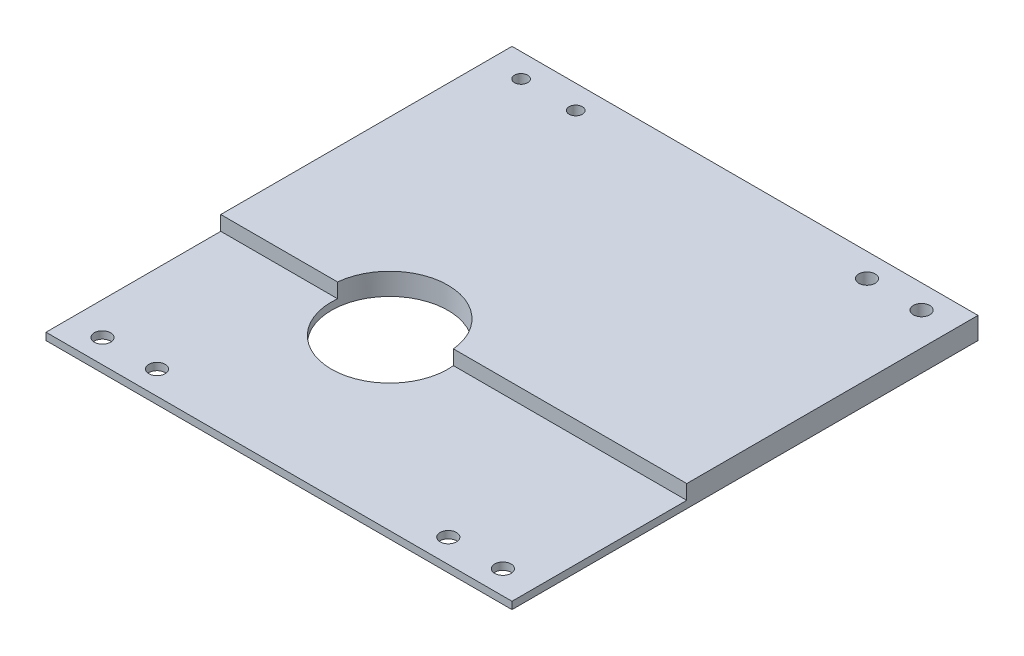
SolidWorks part; units mm, degrees
material "AISI 1020 Steel, Cold Rolled"
ref_plane "Front Plane" through (0, 0, 0) normal (0, 0, 1) x (1, 0, 0)
ref_plane "Top Plane" through (0, 0, 0) normal (0, 1, 0) x (1, 0, 0)
ref_plane "Right Plane" through (0, 0, 0) normal (1, 0, 0) x (0, 0, -1)
sketch "Sketch1" plane through (0, 0, 0) normal (0, 1, 0) x (1, 0, 0)
  line L1 (-203.2, 203.2) -> (203.2, 203.2)
  line L2 (-203.2, 203.2) -> (-203.2, -203.2)
  line L3 (-203.2, -203.2) -> (203.2, -203.2)
  line L4 (203.2, 203.2) -> (203.2, -203.2)
  dimension "D1" = 203.2
  dimension "D2" = 406.4
  dimension "D3" = 203.2
  dimension "D4" = 406.4
extrude "Boss-Extrude1" add sketch "Sketch1" along normal blind 6.35
sketch "Sketch2" plane through (0, 6.35, 0) normal (0, 1, 0) x (1, 0, 0)
  line L0 (-203.2, 203.2) -> (-203.2, -55.88)
  line L1 (-203.2, 203.2) -> (-203.2, -203.2) construction
  line L2 (-203.2, -55.88) -> (-50.8, -55.88)
  circle A0 centre (-50.8, -55.88) radius 50.8
  dimension "D3" = 101.6
  dimension "D1" = 259.08
  dimension "D2" = 152.4
extrude "Cut-Extrude1" cut sketch "Sketch2" against normal blind 6.35
sketch "Sketch3" plane through (0, 6.35, 0) normal (0, 1, 0) x (1, 0, 0)
  line L1 (-203.2, 203.2) -> (203.2, 203.2)
  line L2 (-203.2, 203.2) -> (-203.2, -50.8)
  line L3 (-203.2, -50.8) -> (203.2, -50.8)
  line L4 (203.2, 203.2) -> (203.2, -50.8)
  dimension "D1" = 406.4
  dimension "D2" = 254
extrude "Boss-Extrude4" add sketch "Sketch3" along normal blind 12.7
sketch "Sketch6" plane through (0, 0, 0) normal (0, -1, 0) x (1, 0, 0)
  circle A0 centre (-50.8, 55.88) radius 50.8
extrude "Cut-Extrude3" cut sketch "Sketch6" against normal through all
sketch "Sketch7" plane through (0, 6.35, 0) normal (0, 1, 0) x (1, 0, 0)
  line L0 (-174.625, -182.5625) -> (174.625, -182.5625) construction
  line L1 (-203.2, -203.2) -> (203.2, -203.2) construction
  line L2 (203.2, -203.2) -> (203.2, -50.8) construction
  line L3 (-203.2, -50.8) -> (-203.2, -203.2) construction
  circle A0 centre (174.625, -182.5625) radius 7.1438
  circle A1 centre (127, -182.5625) radius 7.1438
  circle A2 centre (-174.625, -182.5625) radius 7.1438
  circle A3 centre (-127, -182.5625) radius 7.1437
  dimension "D1" = 14.2875
  dimension "D2" = 20.6375
  dimension "D3" = 28.575
  dimension "D4" = 28.575
  dimension "D5" = 76.2
  dimension "D6" = 76.2
extrude "Cut-Extrude4" cut sketch "Sketch7" against normal through all
sketch "Sketch8" plane through (0, 19.05, 0) normal (0, 1, 0) x (1, 0, 0)
  line L0 (-203.2, 203.2) -> (-203.2, -50.8) construction
  line L1 (203.2, 203.2) -> (-203.2, 203.2) construction
  point P0 (-174.625, 182.5625)
  point P1 (-127, 182.5625)
  dimension "D1" = 28.575
  dimension "D2" = 76.2
  dimension "D3" = 20.6375
  dimension "D4" = 20.6375
hole_wizard "1/2-20 Tapped Hole1" positions "Sketch10" profile "Sketch9" tap size "1/2-20" standard "ANSI Inch" end condition through all
sketch "Sketch10" plane through (0, 19.05, 0) normal (0, 1, 0) x (1, 0, 0)
  point P0 (-174.625, 182.5625)
  point P3 (-127, 182.5625)
sketch "Sketch9" plane through (-174.625, 19.05, -182.5625) normal (1, 0, 0) x (0, 0, 1)
  line L0 (0, 0) -> (0, 19.05)
  line L1 (0, 19.05) -> (5.7544, 19.05)
  line L2 (5.7544, 19.05) -> (5.7544, 0)
  line L5 (5.7544, 0) -> (0, 0)
  line L11 (0, -6.35) -> (0, 107.95) construction
  dimension "Thru Tap Drill Dia." = 11.5087
  dimension "Thru Tap Drill Depth" = 19.05
cosmetic thread "Hole Thread1" parameters "D2"=12.7
cosmetic thread "Hole Thread2" parameters "D2"=12.7
sketch "Sketch11" plane through (0, 19.05, 0) normal (0, 1, 0) x (1, 0, 0)
  line L0 (203.2, -50.8) -> (203.2, 203.2) construction
  line L1 (203.2, 203.2) -> (-203.2, 203.2) construction
  circle A0 centre (174.625, 182.5625) radius 7.1438
  circle A1 centre (127, 182.5625) radius 7.1438
  dimension "D5" = 14.2875
  dimension "D6" = 14.2875
  dimension "D1" = 28.575
  dimension "D2" = 76.2
  dimension "D3" = 20.6375
  dimension "D4" = 20.6375
extrude "Cut-Extrude5" cut sketch "Sketch11" against normal through all
